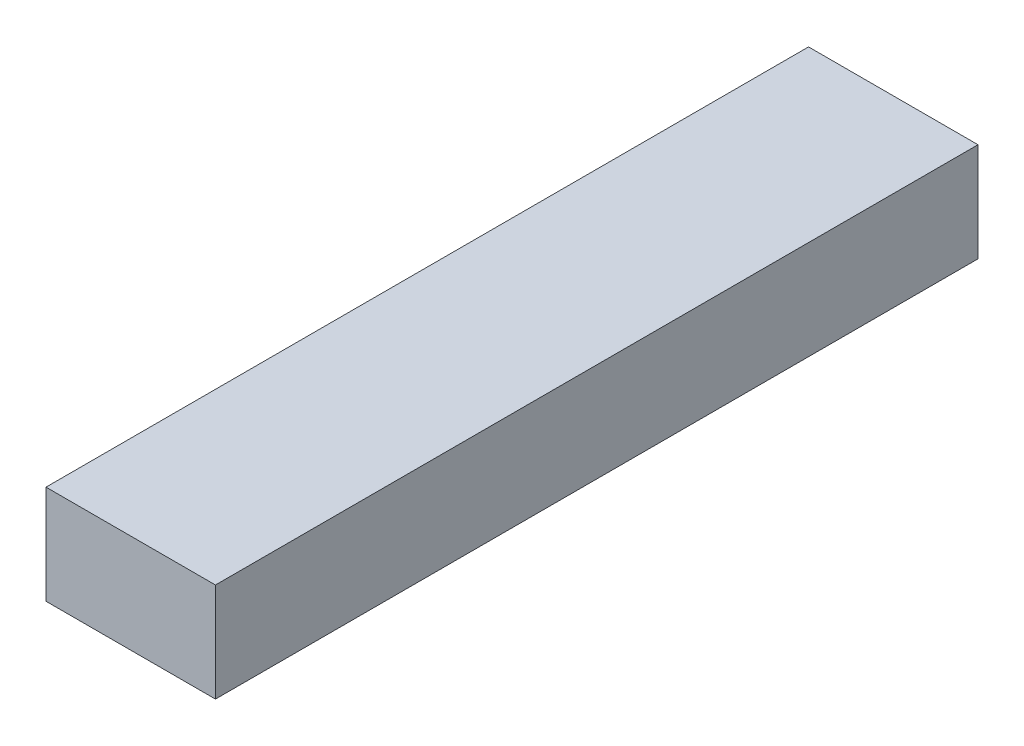
SolidWorks part; units mm, degrees
ref_plane "Front Plane" through (0, 0, 0) normal (0, 0, 1) x (1, 0, 0)
ref_plane "Top Plane" through (0, 0, 0) normal (0, 1, 0) x (1, 0, 0)
ref_plane "Right Plane" through (0, 0, 0) normal (1, 0, 0) x (0, 0, -1)
sketch "Sketch1" plane through (0, 0, 0) normal (0, 0, 1) x (1, 0, 0)
  line L1 (152.4, -88.9) -> (-152.4, -88.9)
  line L2 (152.4, -88.9) -> (152.4, 88.9)
  line L3 (152.4, 88.9) -> (-152.4, 88.9)
  line L4 (-152.4, -88.9) -> (-152.4, 88.9)
  line L5 (152.4, -88.9) -> (-152.4, 88.9) construction
  line L6 (152.4, 88.9) -> (-152.4, -88.9) construction
  point P0 (0, 0)
  dimension "D1" = 177.8
  dimension "D2" = 304.8
extrude "Boss-Extrude1" add sketch "Sketch1" along normal blind 1371.6
